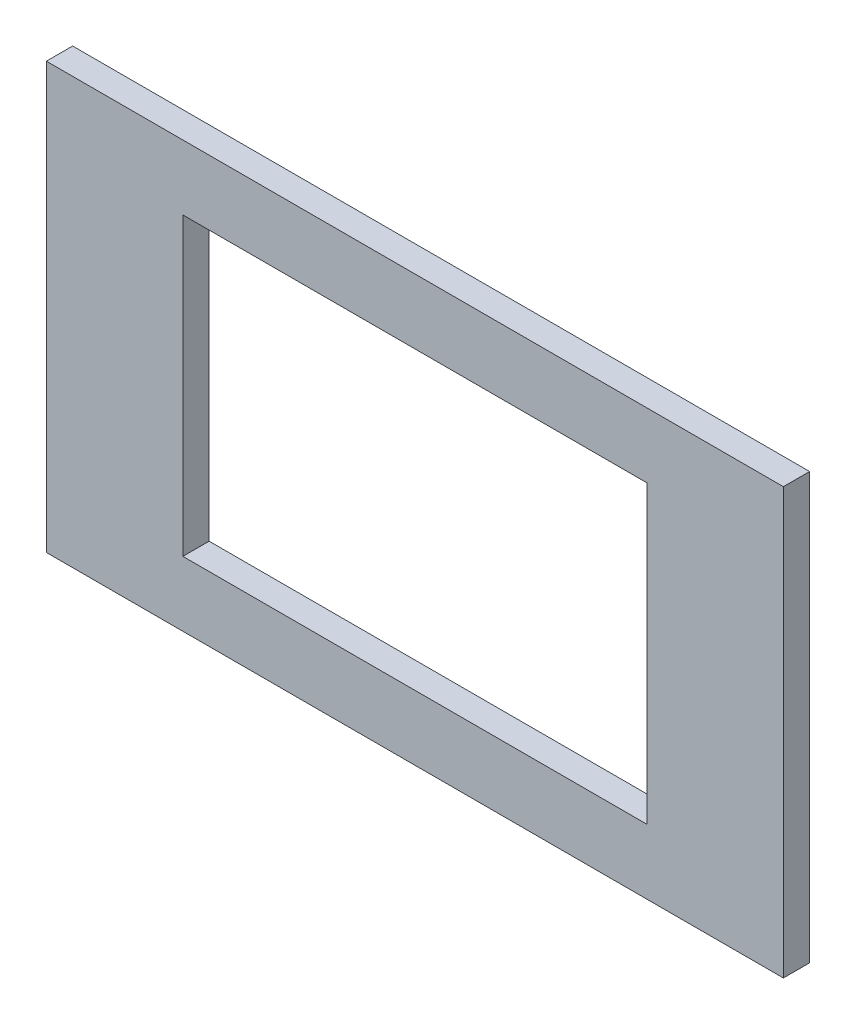
SolidWorks part; units mm, degrees
ref_plane "Front Plane" through (0, 0, 0) normal (0, 0, 1) x (1, 0, 0)
ref_plane "Top Plane" through (0, 0, 0) normal (0, 1, 0) x (1, 0, 0)
ref_plane "Right Plane" through (0, 0, 0) normal (1, 0, 0) x (0, 0, -1)
sketch "Sketch1" plane through (0, 0, 0) normal (0, 0, 1) x (1, 0, 0)
  line L1 (-70.1417, 40.4944) -> (70.1417, 40.4944)
  line L2 (-70.1417, 40.4944) -> (-70.1417, -40.4944)
  line L3 (-70.1417, -40.4944) -> (70.1417, -40.4944)
  line L4 (70.1417, 40.4944) -> (70.1417, -40.4944)
  line L5 (-70.1417, 40.4944) -> (70.1417, -40.4944) construction
  line L6 (-70.1417, -40.4944) -> (70.1417, 40.4944) construction
  line L7 (-44.1591, 28.1416) -> (44.1591, 28.1416)
  line L8 (-44.1591, 28.1416) -> (-44.1591, -28.1416)
  line L9 (-44.1591, -28.1416) -> (44.1591, -28.1416)
  line L10 (44.1591, 28.1416) -> (44.1591, -28.1416)
  line L11 (-44.1591, 28.1416) -> (44.1591, -28.1416) construction
  line L12 (-44.1591, -28.1416) -> (44.1591, 28.1416) construction
  point P0 (0, 0)
  point P6 (0, 0)
extrude "Boss-Extrude1" add sketch "Sketch1" along normal blind 5
